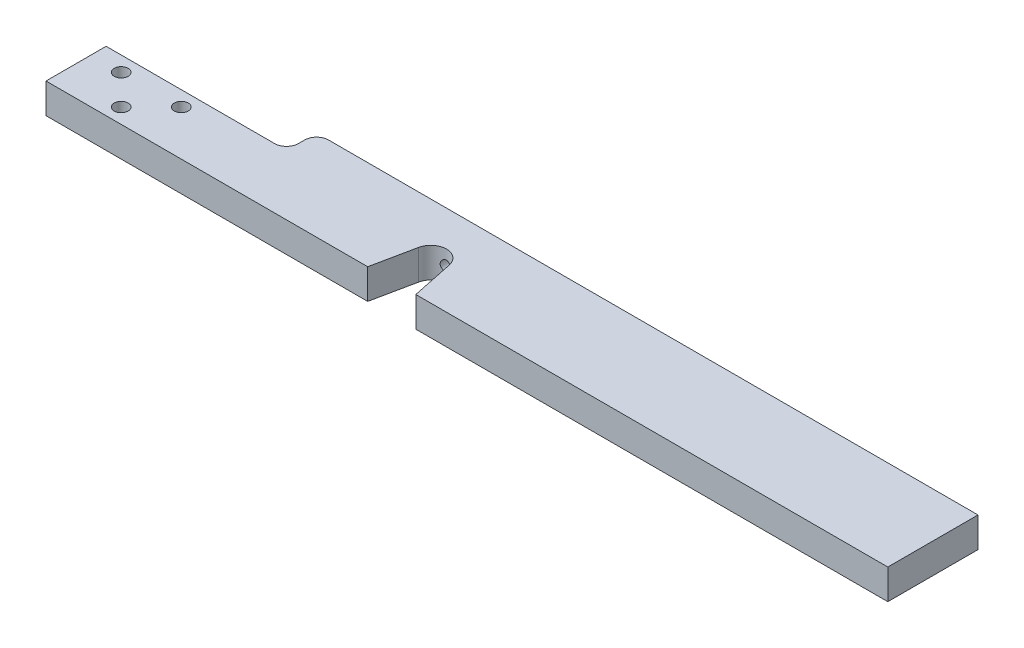
SolidWorks part; units mm, degrees
ref_plane "Front Plane" through (0, 0, 0) normal (0, 0, 1) x (1, 0, 0)
ref_plane "Top Plane" through (0, 0, 0) normal (0, 1, 0) x (1, 0, 0)
ref_plane "Right Plane" through (0, 0, 0) normal (1, 0, 0) x (0, 0, -1)
sketch "Sketch1" plane through (0, 0, 0) normal (0, 1, 0) x (1, 0, 0)
  line L0 (73.025, 0.3269) -> (73.025, 8.255) construction
  line L1 (0, 0) -> (67.945, 0)
  line L2 (0, 0) -> (0, 12.7)
  line L3 (40.64, 19.05) -> (177.8, 19.05)
  line L4 (177.8, 0) -> (177.8, 19.05)
  line L9 (67.945, 0) -> (69.7915, 8.9241)
  line L10 (78.105, 0) -> (76.2585, 8.9241)
  line L11 (78.105, 0) -> (177.8, 0)
  line L12 (0, 12.7) -> (35.56, 12.7)
  line L13 (38.1, 15.24) -> (38.1, 16.51)
  circle A0 centre (12.7, 9.525) radius 6.35 construction
  arc A2 (76.2585, 8.9241) -> (69.7915, 8.9241) centre (73.025, 8.255) ccw
  arc A3 (38.1, 16.51) -> (40.64, 19.05) centre (40.64, 16.51) cw
  arc A4 (38.1, 15.24) -> (35.56, 12.7) centre (35.56, 15.24) cw
  dimension "D3" = 12.7
  dimension "D10" = 2.54
  dimension "D13" = 3.302
  dimension "D1" = 19.05
  dimension "D2" = 177.8
  dimension "D4" = 12.7
  dimension "D5" = 60.325
  dimension "D6" = 8.255
  dimension "D8" = 9.525
  dimension "D9" = 6.35
  dimension "D11" = 38.1
  dimension "D12" = 5.08
  dimension "D7" = 5.08
extrude "Boss-Extrude1" add sketch "Sketch1" along normal blind 6.35
hole_wizard "#32 (0.116) Diameter Hole1" positions "3DSketch1" profile "Sketch2" hole size "#32" standard "ANSI Inch"
sketch3d "3DSketch1"
  line L3 (0, 6.35, -12.7) -> (0, 6.35, 0) construction
  line L4 (0, 6.35, 0) -> (67.945, 6.35, 0) construction
  circle A4 centre (12.7, 6.35, -9.525) radius 6.35 construction
  point P0 (6.35, 6.35, -9.525)
  point P2 (19.05, 6.35, -9.525)
  point P4 (12.7, 6.35, -3.175)
  point P32 (12.7, 12.7, -9.525)
  point P47 (0, 0, 0)
  dimension "D1" = 12.7
  dimension "D2" = 9.525
  dimension "D3" = 12.7
sketch "Sketch2" plane through (6.35, 6.35, -9.525) normal (1, 0, 0) x (0, 0, 1)
  line L0 (0, 0) -> (0, 8.5052)
  line L1 (0, 8.5052) -> (1.4732, 7.62)
  line L2 (1.4732, 7.62) -> (1.4732, 0)
  line L5 (1.4732, 0) -> (0, 0)
  line L10 (0, 8.5052) -> (-1.4732, 7.62) construction
  line L11 (0, -6.35) -> (0, 107.95) construction
  dimension "Hole Dia." = 2.9464
  dimension "Hole Depth" = 7.62
  dimension "Drill Angle" = 118
hole_wizard "#4-40 Tapped Hole1" positions "Sketch3" profile "Sketch4" tap size "#4-40" standard "ANSI Inch" end condition up to next
sketch "Sketch3" plane through (0, 0, -19.05) normal (0, 0, -1) x (-1, 0, 0)
  line L0 (-177.8, 6.35) -> (-177.8, 0) construction
  line L1 (-177.8, 0) -> (-40.64, 0) construction
  point P0 (-73.025, 3.175)
  dimension "D1" = 104.775
  dimension "D2" = 3.175
sketch "Sketch4" plane through (73.025, 3.175, -19.05) normal (1, 0, 0) x (0, 1, 0)
  line L0 (0, 0) -> (0, 7.493)
  line L1 (0, 7.493) -> (1.1303, 7.493)
  line L2 (1.1303, 7.493) -> (1.1303, 0)
  line L5 (1.1303, 0) -> (0, 0)
  line L11 (0, -6.35) -> (0, 107.95) construction
  dimension "Thru Tap Drill Dia." = 2.2606
  dimension "Thru Tap Drill Depth" = 7.493
cosmetic thread "Hole Thread1"
equation "\"D7@Sketch1\"=\"D12@Sketch1\""
